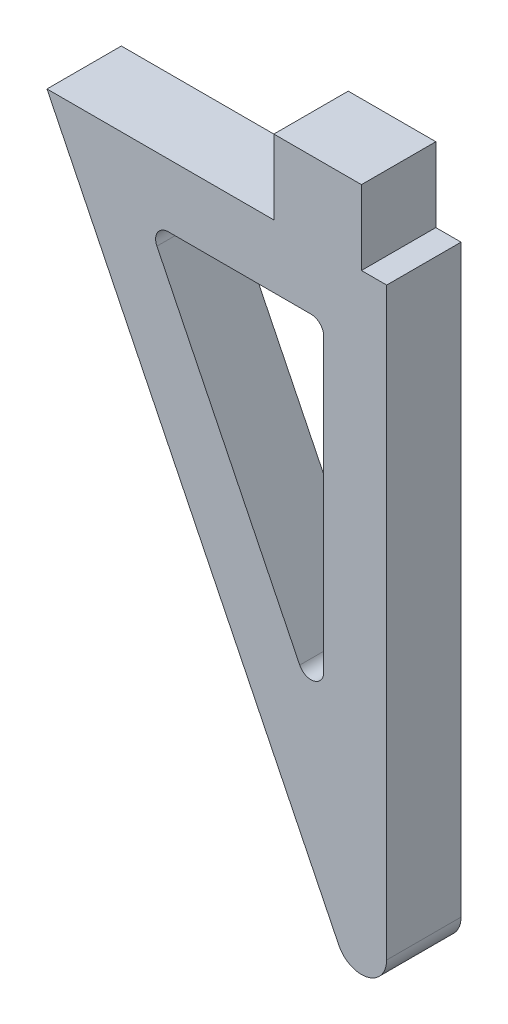
SolidWorks part; units mm, degrees
ref_plane "Front Plane" through (0, 0, 0) normal (0, 0, 1) x (1, 0, 0)
ref_plane "Top Plane" through (0, 0, 0) normal (0, 1, 0) x (1, 0, 0)
ref_plane "Right Plane" through (0, 0, 0) normal (1, 0, 0) x (0, 0, -1)
sketch "Sketch1" plane through (0, 0, 0) normal (0, 0, 1) x (1, 0, 0)
  line L0 (0, 0) -> (6.95, 0)
  line L1 (6.95, 0) -> (6.95, -5.9)
  line L2 (6.95, -5.9) -> (8.95, -5.9)
  line L3 (8.95, -5.9) -> (8.95, -60.9)
  line L4 (8.95, -60.9) -> (-18, -5.9)
  line L5 (-18, -5.9) -> (0, -5.9)
  line L6 (0, -5.9) -> (0, 0)
  line L7 (-9.982, -10.9) -> (3.95, -10.9)
  line L8 (3.95, -10.9) -> (3.95, -39.3327)
  line L9 (-9.982, -10.9) -> (3.95, -39.3327)
  point P10 (3.95, -44.8068)
  dimension "D1" = 6.95
  dimension "D2" = 5.9
  dimension "D3" = 18
  dimension "D4" = 55
  dimension "D5" = 2
  dimension "D6" = 5
  dimension "D7" = 5
  dimension "D8" = 5
extrude "Boss-Extrude1" add sketch "Sketch1" along normal blind 5.9
fillet "Fillet1" radius 2 1 edges at (8.95, -60.9, 2.95)
fillet "Fillet2" radius 1 3 edges at (3.95, -39.3327, 2.95) (3.95, -10.9, 2.95) (-9.982, -10.9, 2.95)
equation "\"ACRYLIC\"= 5.9"
equation "\"D2@Sketch1\"=\"ACRYLIC\""
equation "\"D1@Boss-Extrude1\"=\"ACRYLIC\""
